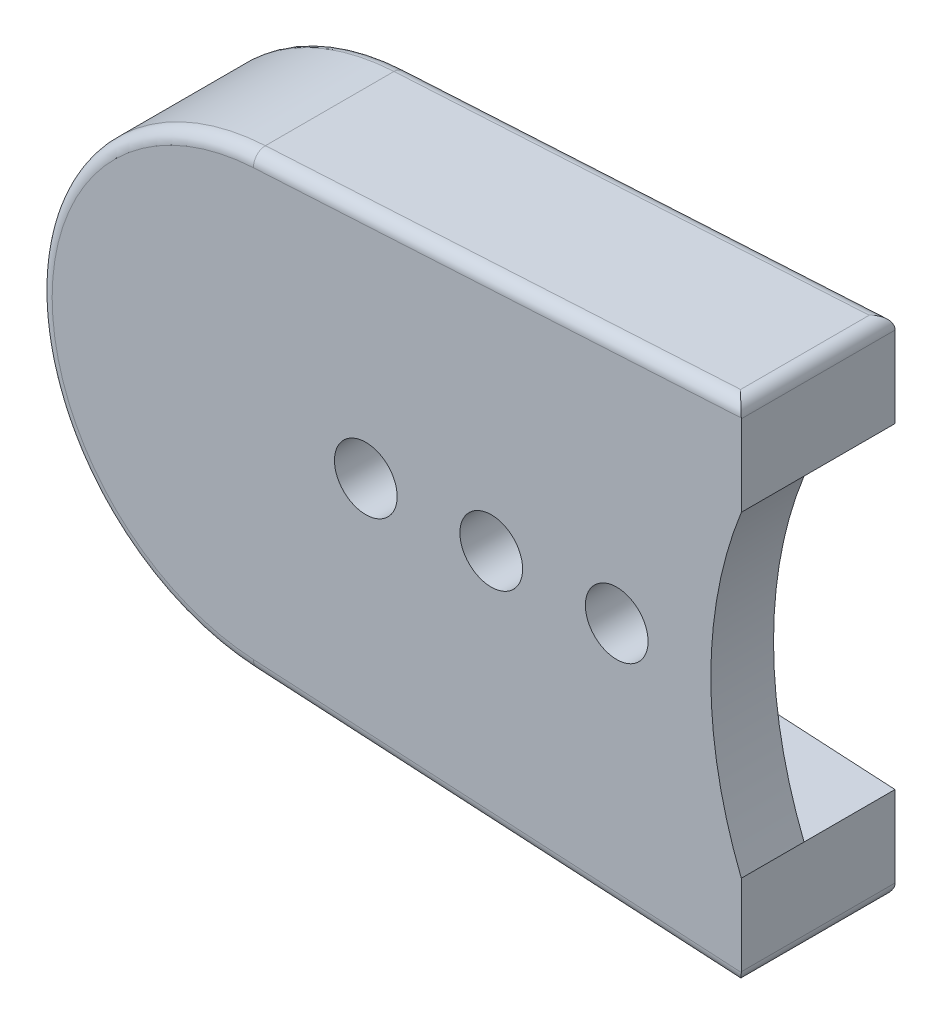
SolidWorks part; units mm, degrees
ref_plane "前视基准面" through (0, 0, 0) normal (0, 0, 1) x (1, 0, 0)
ref_plane "上视基准面" through (0, 0, 0) normal (0, 1, 0) x (1, 0, 0)
ref_plane "右视基准面" through (0, 0, 0) normal (1, 0, 0) x (0, 0, -1)
other "Configuration Table"
sketch "草图1" plane through (0, 0, 0) normal (0, 0, 1) x (1, 0, 0)
  line L10 (-14.0168, -2.0967) -> (-2.2919, -2.7498)
  line L11 (-2.2919, 2.7498) -> (-14.0168, 2.0967)
  line L12 (-14.0168, -2.0967) -> (-6.3135, -2.5258)
  line L13 (-6.3135, 2.5258) -> (-14.0168, 2.0967)
  circle A1 centre (-10.3, 0) radius 0.5 construction
  circle A6 centre (-10.3, 0) radius 0.5
  circle A8 centre (-8.3, 0) radius 0.5 construction
  arc A9 (-14.0168, 2.0967) -> (-14.0168, -2.0967) centre (-13.9, 0) ccw
  arc A10 (-14.0168, 2.0967) -> (-14.0168, -2.0967) centre (-13.9, 0) ccw
  circle A11 centre (-8.3, 0) radius 0.5
  circle A12 centre (-12.3, 0) radius 0.5 construction
  circle A13 centre (-12.3, 0) radius 0.5
  arc A15 (-6.3135, 2.5258) -> (-6.3135, -2.5258) centre (0, 0) ccw
  arc A16 (-2.2864, 2.65) -> (-2.2864, -2.65) centre (0, 0) ccw construction
  circle A17 centre (-6.3, 0) radius 0.5 construction
  point P9 (-6.5294, 2.5158)
  point P10 (-6.5249, -2.5141)
  dimension "D1" = 0.1
extrude "凸台-拉伸1" add sketch "草图1" along normal blind 1
sketch "草图3" plane through (0, 0, 1) normal (0, 0, 1) x (1, 0, 0)
  line L0 (-6.3135, 4.0282) -> (-14.1002, 3.5944)
  line L1 (-14.1002, -3.5944) -> (-6.3135, -4.0282)
  line L2 (-6.3969, 4.0235) -> (-14.1002, 3.5944) construction
  line L3 (-6.3135, 2.5258) -> (-14.0168, 2.0967)
  line L4 (-14.0168, -2.0967) -> (-6.3135, -2.5258)
  line L6 (-6.3135, 2.5258) -> (-14.0168, 2.0967)
  line L7 (-14.0168, -2.0967) -> (-6.3135, -2.5258)
  line L9 (-14.1002, -3.5944) -> (-6.3969, -4.0235) construction
  line L10 (-6.3135, 2.5258) -> (-6.3135, 4.0282)
  line L11 (-6.3135, -2.5258) -> (-6.3135, -4.0282)
  arc A0 (-14.1002, 3.5944) -> (-14.1002, -3.5944) centre (-13.9, 0) ccw
  arc A1 (-14.0168, 2.0967) -> (-14.0168, -2.0967) centre (-13.9, 0) ccw
  arc A2 (-14.0168, 2.0967) -> (-14.0168, -2.0967) centre (-13.9, 0) ccw
  arc A5 (-6.3135, 2.5258) -> (-6.3135, -2.5258) centre (0, 0) ccw
  arc A6 (-6.3135, 2.5258) -> (-6.3135, -2.5258) centre (0, 0) ccw
  line M5 (-6.3135, 2.5258) -> (-14.0168, 2.0967)
  arc M6 (-14.0168, 2.0967) -> (-14.0168, -2.0967) centre (-13.9, 0) ccw
  line M7 (-14.0168, -2.0967) -> (-6.3135, -2.5258)
  dimension "D1" = 0
  dimension "D2" = 1.5
extrude "凸台-拉伸2" add sketch "草图3" against normal up to surface (2.45 mm away) contours L0 A0 L1 L11 L10 M7 M6 M5
fillet "圆角1" radius 0.2 8 edges at (-10.2069, -3.8113, -1.45) (-10.2069, -3.8113, 1) (-6.3135, -4.0282, -0.225) (-17.5, 0, -1.45) (-17.5, 0, 1) (-10.2069, 3.8113, -1.45) (-10.2069, 3.8113, 1) (-6.3135, 4.0282, -0.225)
